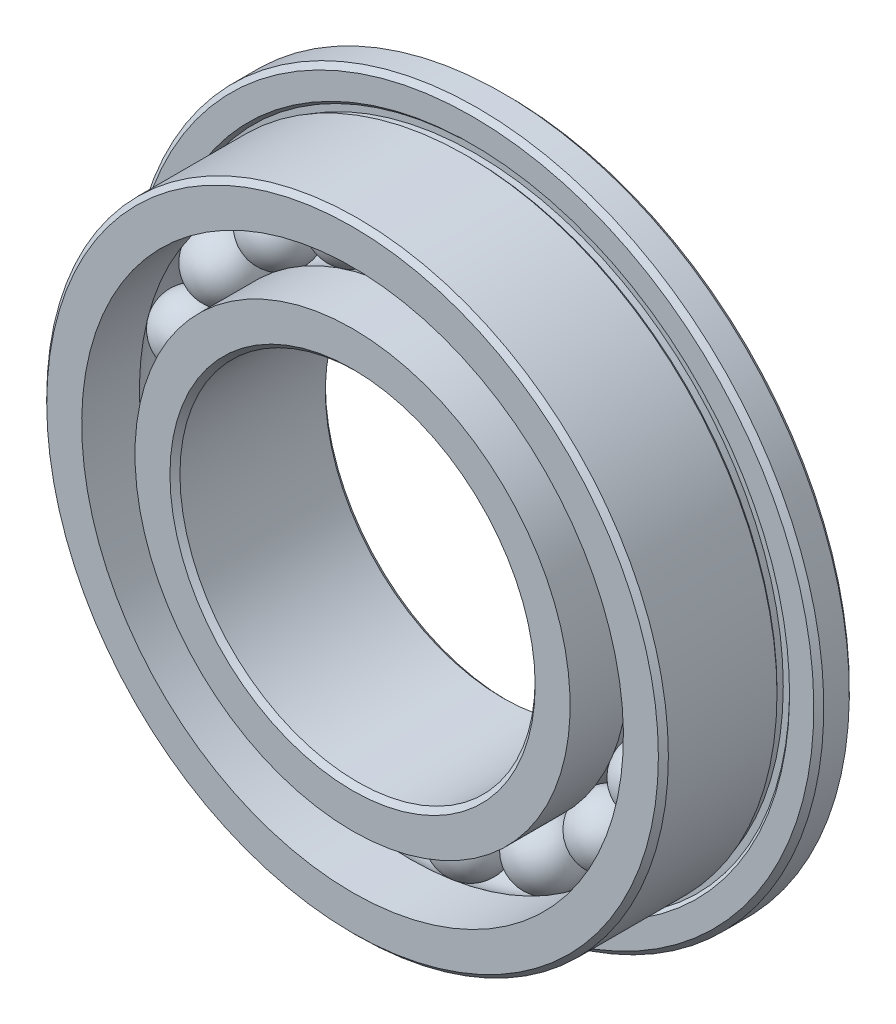
SolidWorks part; units mm, degrees
ref_plane "Front Plane" through (0, 0, 0) normal (0, 0, 1) x (1, 0, 0)
ref_plane "Top Plane" through (0, 0, 0) normal (0, 1, 0) x (1, 0, 0)
ref_plane "Right Plane" through (0, 0, 0) normal (1, 0, 0) x (0, 0, -1)
sketch "Sketch1" plane through (0, 0, 0) normal (1, 0, 0) x (0, 0, -1)
  line L0 (0, 7) -> (0, -7) construction
  line L1 (-1.75, 7) -> (1.75, 7) construction
  line L2 (0, 0) -> (1.75, 0) construction
  line L3 (1.75, 7.8) -> (1.75, -7.8) construction
  line L4 (1.75, -7.8) -> (0.95, -7.8) construction
  line L5 (1.75, 4) -> (0, 4) construction
  line L6 (1.75, 4) -> (1.75, -4) construction
  dimension "OD" = 14
  dimension "Width" = 3.5
  dimension "Flange Thickness" = 0.8
  dimension "ID" = 8
  dimension "Flange OD" = 15.6
sketch "Sketch2" plane through (0, 0, 0) normal (1, 0, 0) x (0, 0, -1)
  line L0 (1.75, 7.8) -> (0.95, 7.8)
  line L1 (0.95, 7.8) -> (0.95, 7.1414)
  line L2 (0.8086, 7) -> (-1.75, 7)
  line L3 (-1.75, 7) -> (-1.75, 6.1)
  line L4 (-1.75, 6.1) -> (-0.45, 6.1)
  line L5 (1.75, 7.8) -> (1.75, -7.8) construction
  line L6 (1.75, 6.1) -> (1.75, 7.8)
  line L7 (1.75, 4) -> (-1.75, 4)
  line L8 (-1.75, 4) -> (-1.75, 4.9)
  line L9 (-1.75, 4.9) -> (-0.45, 4.9)
  line L10 (1.75, 4.9) -> (1.75, 4)
  line L11 (0, 7) -> (0, 4) construction
  line L12 (-0.75, 5.5) -> (0.75, 5.5) construction
  line L13 (0.45, 6.1) -> (1.75, 6.1)
  line L14 (0.45, 4.9) -> (1.75, 4.9)
  line L15 (0.95, 7.1414) -> (1.0207, 7.0707)
  line L16 (1.0207, 7.0707) -> (1.0207, 6.9293)
  line L17 (1.0207, 6.9293) -> (0.8793, 6.9293)
  line L18 (0.8793, 6.9293) -> (0.8086, 7)
  line L19 (0.95, 7) -> (1.0207, 6.9293) construction
  line L20 (1.0207, 7.0707) -> (0.8793, 6.9293) construction
  line L21 (0.8086, 7) -> (0.95, 7) construction
  line L22 (0.95, 7) -> (0.95, 7.1414) construction
  circle A0 centre (0, 5.5) radius 0.75 construction
  arc A1 (-0.45, 6.1) -> (0.45, 6.1) centre (0, 5.5) cw
  arc A2 (-0.45, 4.9) -> (0.45, 4.9) centre (0, 5.5) ccw
  dimension "D1" = 3
  dimension "Ball Dia." = 1.5
  dimension "D2" = 135
  dimension "D3" = 0.2
  dimension "D4" = 1.2
  dimension "Race Thikness" = 0.9
revolve "Revolve1" add sketch "Sketch2" angle 360 about L2
fillet "Fillet1" radius 0.1125 3 edges at (0, -7.8, -1.75) (0, -7.8, -0.95) (0, -7, 1.75) profile chamfer
sketch "Sketch3" plane through (0, 0, 0) normal (0, 0, 1) x (1, 0, 0)
  line L0 (-4, 0) -> (4, 0) construction
  line L1 (-7, 0) -> (7, 0) construction
  point P5 (0, 0)
  dimension "ID2" = 8
  dimension "OD2" = 14
fillet "Fillet2" radius 0.1125 2 edges at (0, -4, -1.75) (0, -4, 1.75) profile chamfer
sketch "Sketch7" plane through (0, 0, 0) normal (0, 0, 1) x (1, 0, 0)
  line L0 (0, 6.25) -> (0, 4.75)
  line L1 (0, 7.8) -> (0, -7.8) construction
  line L2 (-0.8603, 6.25) -> (0, 0) construction
  line L3 (0, 0) -> (0.8603, 6.25) construction
  line L4 (0.8603, 6.25) -> (-0.8603, 6.25) construction
  circle A0 centre (0, 5.5) radius 0.75 construction
  circle A1 centre (0, 0) radius 6.25 construction
  circle A2 centre (0, 0) radius 4.75 construction
  arc A4 (0, 6.25) -> (0, 4.75) centre (0, 5.5) ccw
  dimension "D1" = 15.675
revolve "Revolve3" add sketch "Sketch7" angle 360 about L0
pattern_circular "CirPattern3" count 19 over 360 about axis through (0, 0, 0) along (0, 0, 1) of bodies 107
sketch "Sketch8" plane through (0, 0, 0) normal (1, 0, 0) x (0, 0, -1)
  line L0 (-1.75, 7) -> (1.75, 7) construction
  line L1 (1.75, 7) -> (1.75, 7.8) construction
  line L2 (-1.75, -7) -> (1.75, -7) construction
  line L3 (1.75, 7.8) -> (1.75, -7.8) construction
  dimension "D1" = 14
equation "\"Ball Dia.@Sketch2\" = ( \"OD@Sketch1\" - \"ID@Sketch1\" ) * .25"
equation "\"D3@Sketch2\"=\"Flange Thickness@Sketch1\"/4"
equation "\"D1@Fillet1\" = \"Race Thikness@Sketch2\" / 8"
equation "\"ID2@Sketch3\" = \"ID@Sketch1\""
equation "\"OD2@Sketch3\" = \"OD@Sketch1\""
equation "\"D1@Fillet2\" = \"Race Thikness@Sketch2\" / 8"
equation "\"D1@CirPattern3\"=360/\"D1@Sketch7\"-4"
equation "\"D4@Sketch2\" = ( \"OD@Sketch1\" - \"ID@Sketch1\" ) * .2"
